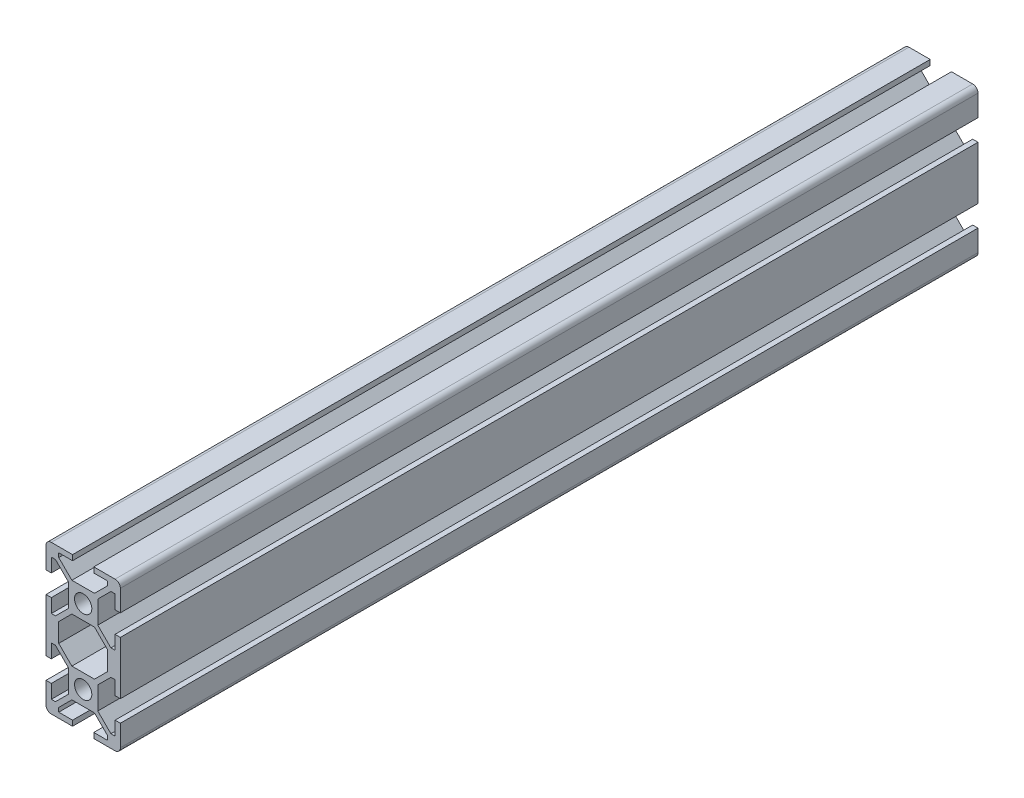
SolidWorks part; units mm, degrees
material "6061 Aluminum Alloy"
ref_plane "Front Plane" through (0, 0, 0) normal (0, 0, 1) x (1, 0, 0)
ref_plane "Top Plane" through (0, 0, 0) normal (0, 1, 0) x (1, 0, 0)
ref_plane "Right Plane" through (0, 0, 0) normal (1, 0, 0) x (0, 0, -1)
sketch "Sketch1" plane through (0, 0, 0) normal (0, 0, 1) x (1, 0, 0)
  line L0 (-51.9455, 19.536) -> (-51.9455, -0.464)
  line L1 (-51.9455, -0.464) -> (-49.9455, -0.464)
  line L2 (-49.9455, -0.464) -> (-49.9455, 4.7413)
  line L3 (-49.9455, 4.7413) -> (-48.3862, 4.7413)
  line L4 (-48.3862, 4.7413) -> (-43.4455, -0.1995)
  line L5 (-43.4455, -0.1995) -> (-43.4455, -8.7179)
  line L6 (-43.4455, -8.7179) -> (-48.3862, -13.6587)
  line L7 (-48.3862, -13.6587) -> (-49.9455, -13.6587)
  line L8 (-49.9455, -13.6587) -> (-49.9455, -8.4587)
  line L9 (-49.9455, -8.4587) -> (-51.9455, -8.4587)
  line L10 (-51.9455, -8.4587) -> (-51.9455, -16.4587)
  line L11 (-49.9455, -18.4587) -> (-41.9455, -18.4587)
  line L12 (-41.9455, -18.4587) -> (-41.9455, -16.4587)
  line L13 (-41.9455, -16.4587) -> (-47.1455, -16.4587)
  line L14 (-47.1455, -16.4587) -> (-47.1455, -14.8995)
  line L15 (-47.1455, -14.8995) -> (-42.2047, -9.9587)
  line L16 (-42.2047, -9.9587) -> (-33.6862, -9.9587)
  line L17 (-33.6862, -9.9587) -> (-28.7455, -14.8995)
  line L18 (-28.7455, -14.8995) -> (-28.7455, -16.4587)
  line L19 (-28.7455, -16.4587) -> (-33.9455, -16.4587)
  line L20 (-33.9455, -16.4587) -> (-33.9455, -18.4587)
  line L21 (-33.9455, -18.4587) -> (-25.9455, -18.4587)
  line L22 (-23.9455, -16.4587) -> (-23.9455, -8.4587)
  line L23 (-23.9455, -8.4587) -> (-25.9455, -8.4587)
  line L24 (-25.9455, -8.4587) -> (-25.9455, -13.6587)
  line L25 (-25.9455, -13.6587) -> (-27.5047, -13.6587)
  line L26 (-27.5047, -13.6587) -> (-32.4455, -8.7179)
  line L27 (-32.4455, -8.7179) -> (-32.4455, -0.1995)
  line L28 (-32.4455, -0.1995) -> (-27.5047, 4.7413)
  line L29 (-27.5047, 4.7413) -> (-25.9455, 4.7413)
  line L30 (-25.9455, 4.7413) -> (-25.9455, -0.464)
  line L31 (-25.9455, -0.464) -> (-23.9455, -0.464)
  line L32 (-23.9455, -0.464) -> (-23.9455, 19.5413)
  line L33 (-23.9455, 19.5413) -> (-25.9455, 19.5413)
  line L34 (-25.9455, 19.5413) -> (-25.9455, 14.3413)
  line L35 (-25.9455, 14.3413) -> (-27.5047, 14.3413)
  line L36 (-27.5047, 14.3413) -> (-32.4455, 19.2821)
  line L37 (-32.4455, 19.2821) -> (-32.4455, 27.8005)
  line L38 (-32.4455, 27.8005) -> (-27.5047, 32.7413)
  line L39 (-27.5047, 32.7413) -> (-25.9455, 32.7413)
  line L40 (-25.9455, 32.7413) -> (-25.9455, 27.5413)
  line L41 (-25.9455, 27.5413) -> (-23.9455, 27.5413)
  line L42 (-23.9455, 27.5413) -> (-23.9455, 35.5413)
  line L43 (-25.9455, 37.5413) -> (-33.9455, 37.5413)
  line L44 (-33.9455, 37.5413) -> (-33.9455, 35.5413)
  line L45 (-33.9455, 35.5413) -> (-28.7455, 35.5413)
  line L46 (-28.7455, 35.5413) -> (-28.7455, 33.9821)
  line L47 (-28.7455, 33.9821) -> (-33.6862, 29.0413)
  line L48 (-33.6862, 29.0413) -> (-42.2047, 29.0413)
  line L49 (-42.2047, 29.0413) -> (-47.1455, 33.9821)
  line L50 (-47.1455, 33.9821) -> (-47.1455, 35.5413)
  line L51 (-47.1455, 35.5413) -> (-41.9455, 35.5413)
  line L52 (-41.9455, 35.5413) -> (-41.9455, 37.5413)
  line L53 (-41.9455, 37.5413) -> (-49.9455, 37.5413)
  line L54 (-51.9455, 35.5413) -> (-51.9455, 27.5413)
  line L55 (-51.9455, 27.5413) -> (-49.9455, 27.5413)
  line L56 (-49.9455, 27.5413) -> (-49.9455, 32.736)
  line L57 (-49.9455, 32.736) -> (-48.3721, 32.736)
  line L58 (-48.3721, 32.736) -> (-43.4313, 27.7953)
  line L59 (-43.4313, 27.7953) -> (-43.4313, 19.2768)
  line L60 (-43.4313, 19.2768) -> (-48.3721, 14.336)
  line L61 (-48.3721, 14.336) -> (-49.9313, 14.336)
  line L62 (-49.9313, 14.336) -> (-49.9313, 19.536)
  line L63 (-49.9313, 19.536) -> (-51.9455, 19.536)
  line L64 (-33.6862, 18.0413) -> (-42.2047, 18.0413)
  line L65 (-42.2047, 18.0413) -> (-47.1455, 13.1005)
  line L66 (-47.1455, 13.1005) -> (-47.1455, 5.9821)
  line L67 (-47.1455, 5.9821) -> (-42.2047, 1.0413)
  line L68 (-42.2047, 1.0413) -> (-33.6862, 1.0413)
  line L69 (-33.6862, 1.0413) -> (-28.7455, 5.9821)
  line L70 (-28.7455, 5.9821) -> (-28.7455, 13.1005)
  line L71 (-28.7455, 13.1005) -> (-33.6862, 18.0413)
  arc A0 (-51.9455, -16.4587) -> (-49.9455, -18.4587) centre (-49.9455, -16.4587) ccw
  arc A1 (-25.9455, -18.4587) -> (-23.9455, -16.4587) centre (-25.9455, -16.4587) ccw
  arc A2 (-23.9455, 35.5413) -> (-25.9455, 37.5413) centre (-25.9455, 35.5413) ccw
  arc A3 (-49.9455, 37.5413) -> (-51.9455, 35.5413) centre (-49.9455, 35.5413) ccw
  circle A4 centre (-37.9455, -4.4587) radius 3.25
  circle A5 centre (-37.9455, 23.5413) radius 3.25
extrude "Extrusion2" add sketch "Sketch1" along normal up to vertex (161.5 mm away) and the other way up to vertex (161.5 mm away) contours L53 A3 L54 L55 L56 L57 L58 L59 L60 L61 L62 L63 L0 L1 L2 L3 L4 L5 L6 L7 L8 L9 L10 A0 L11 L12 L13 L14 L15 L16 L17 L18 L19 L20 L21 A1 L22 L23 L24 L25 L26 L27 L28 L29 L30 L31 L32 L33 L34 L35 L36
hole_wizard "Ø4.7 (4.7) Diameter Hole1" positions "Sketch3" profile "Sketch4" hole size "Ø4.7" standard "Macron Ansi Metric" end condition through all
sketch "Sketch3" plane through (-23.9455, 0, 0) normal (1, 0, 0) x (0, 0, -1)
  line L0 (-161.5, -0.464) -> (-161.5, 19.5413) construction
  line L1 (-161.5, 37.5413) -> (161.5, 37.5413) construction
  point P0 (-140.5, 23.5413)
  point P1 (140.5, 23.5413)
  dimension "D1" = 21
  dimension "D2" = 14
  dimension "D3" = 21
sketch "Sketch4" plane through (-23.9455, 23.5413, 140.5) normal (0, 1, 0) x (0, 0, -1)
  line L0 (0, 0) -> (0, 28)
  line L1 (0, 28) -> (2.375, 28)
  line L2 (2.375, 28) -> (2.375, 0)
  line L5 (2.375, 0) -> (0, 0)
  line L11 (0, -6.35) -> (0, 107.95) construction
  dimension "Thru Hole Dia." = 4.75
  dimension "Thru Hole Depth" = 28
